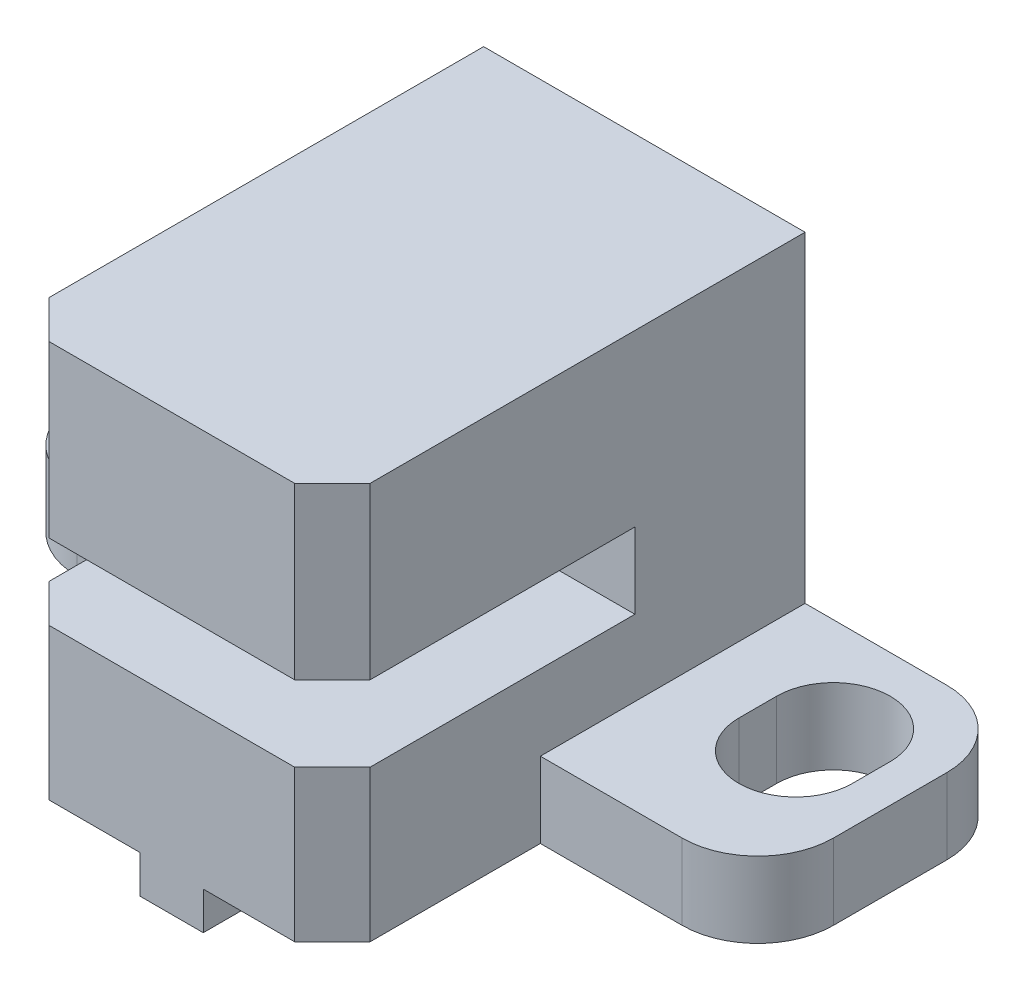
SolidWorks part; units mm, degrees
ref_plane "Front Plane" through (0, 0, 0) normal (0, 0, 1) x (1, 0, 0)
ref_plane "Top Plane" through (0, 0, 0) normal (0, 1, 0) x (1, 0, 0)
ref_plane "Right Plane" through (0, 0, 0) normal (1, 0, 0) x (0, 0, -1)
sketch "Sketch1" plane through (0, 0, 0) normal (0, 0, 1) x (1, 0, 0)
  line L1 (-4.25, 5.25) -> (4.25, 5.25)
  line L2 (-4.25, 5.25) -> (-4.25, -5.25)
  line L3 (-4.25, -5.25) -> (4.25, -5.25)
  line L4 (4.25, 5.25) -> (4.25, -5.25)
  line L5 (-4.25, 5.25) -> (4.25, -5.25) construction
  line L6 (-4.25, -5.25) -> (4.25, 5.25) construction
  point P0 (0, 0)
  dimension "D1" = 8.5
  dimension "D2" = 10.5
extrude "Boss-Extrude1" add sketch "Sketch1" along normal blind 12.5
sketch "Sketch2" plane through (0, 0, 12.5) normal (0, 0, 1) x (1, 0, 0)
  line L0 (-4.25, 5.25) -> (-4.25, -5.25) construction
  line L1 (-4.25, 0.75) -> (4.25, 0.75)
  line L2 (-4.25, 0.75) -> (-4.25, -1.25)
  line L3 (-4.25, -1.25) -> (4.25, -1.25)
  line L4 (4.25, 0.75) -> (4.25, -1.25)
  line L5 (4.25, -5.25) -> (4.25, 5.25) construction
  line L6 (-4.25, -5.25) -> (4.25, -5.25) construction
  dimension "D1" = 2
  dimension "D2" = 4
extrude "Cut-Extrude1" cut sketch "Sketch2" against normal blind 8
sketch "Sketch3" plane through (0, -5.25, 0) normal (0, -1, 0) x (1, 0, 0)
  line L0 (7.5, 2.5) -> (7.5, 3.5) construction
  line L1 (4.25, 0) -> (8, 0)
  line L2 (4.25, 0) -> (4.25, 7)
  line L3 (4.25, 7) -> (8, 7)
  line L4 (10, 2) -> (10, 5)
  line L5 (6, 2.5) -> (6, 3.5)
  line L6 (9, 2.5) -> (9, 3.5)
  line L7 (0, 0) -> (0, 12.5) construction
  line L8 (-4.25, 0) -> (4.25, 0) construction
  line L9 (-4.25, 12.5) -> (4.25, 12.5) construction
  line L10 (-10, 2) -> (-10, 5)
  line L11 (-4.25, 7) -> (-8, 7)
  line L12 (-4.25, 0) -> (-4.25, 7)
  line L13 (-4.25, 0) -> (-8, 0)
  line L14 (-7.5, 2.5) -> (-7.5, 3.5) construction
  line L15 (-6, 2.5) -> (-6, 3.5)
  line L16 (-9, 2.5) -> (-9, 3.5)
  arc A0 (6, 2.5) -> (9, 2.5) centre (7.5, 2.5) ccw
  arc A1 (9, 3.5) -> (6, 3.5) centre (7.5, 3.5) ccw
  arc A2 (-6, 2.5) -> (-9, 2.5) centre (-7.5, 2.5) cw
  arc A3 (-9, 3.5) -> (-6, 3.5) centre (-7.5, 3.5) cw
  arc A4 (8, 7) -> (10, 5) centre (8, 5) cw
  arc A5 (10, 2) -> (8, 0) centre (8, 2) cw
  arc A6 (-8, 0) -> (-10, 2) centre (-8, 2) cw
  arc A7 (-8, 7) -> (-10, 5) centre (-8, 5) ccw
  point P7 (7.5, 3)
  point P26 (-7.5, 3)
  point P33 (10, 7)
  point P36 (10, 0)
  point P39 (-10, 0)
  point P42 (-10, 7)
  dimension "D3" = 1.5
  dimension "D7" = 2
  dimension "D1" = 7
  dimension "D2" = 10
  dimension "D4" = 1
  dimension "D5" = 2
  dimension "D6" = 7.5
extrude "Boss-Extrude2" add sketch "Sketch3" against normal blind 2
chamfer "Chamfer1" distance 1 angle 45 4 edges at (4.25, -3.25, 12.5) (4.25, 3, 12.5) (-4.25, -3.25, 12.5) (-4.25, 3, 12.5)
sketch "Sketch4" plane through (0, -5.25, 0) normal (0, -1, 0) x (1, 0, 0)
  line L0 (0, 0) -> (0, 12.5) construction
  line L1 (-3.25, 12.5) -> (3.25, 12.5) construction
  line L3 (-0.836, 0) -> (0.836, 0)
  line L4 (-0.836, 0) -> (-0.836, 12.5)
  line L5 (-0.836, 12.5) -> (0.836, 12.5)
  line L6 (0.836, 0) -> (0.836, 12.5)
  line L7 (-0.836, 0) -> (0.836, 12.5) construction
  line L8 (-0.836, 12.5) -> (0.836, 0) construction
  point P5 (0, 6.25)
extrude "Boss-Extrude3" add sketch "Sketch4" along normal blind 1
